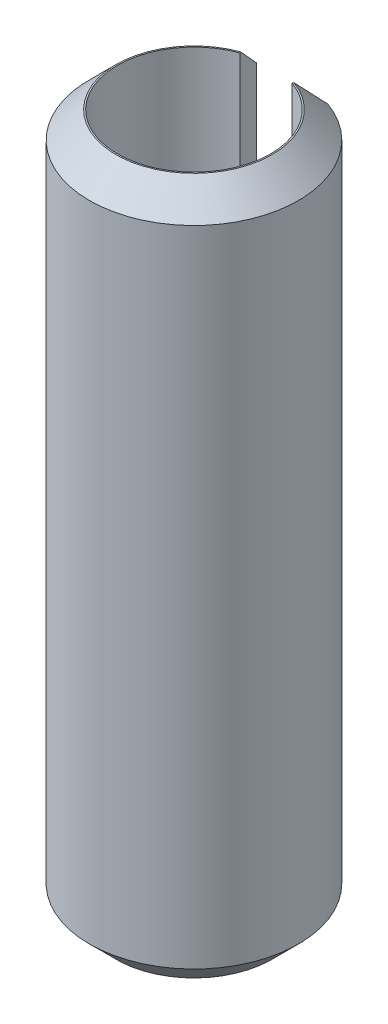
SolidWorks part; units mm, degrees
ref_plane "Top" through (0, 0, 0) normal (0, 0, 1) x (1, 0, 0)
ref_plane "Front" through (0, 0, 0) normal (0, 1, 0) x (1, 0, 0)
ref_plane "Right" through (0, 0, 0) normal (1, 0, 0) x (0, 0, -1)
sketch "Cross Section Sketch" plane through (0, 0, 0) normal (0, 1, 0) x (1, 0, 0)
  line L0 (0.1881, 0.5168) -> (0.2565, 0.7048)
  line L1 (-0.1881, 0.5168) -> (-0.2565, 0.7048)
  line L2 (0, 0) -> (0, 0.5168) construction
  arc A0 (-0.1881, 0.5168) -> (0.1881, 0.5168) centre (0, 0) ccw
  arc A1 (-0.2565, 0.7048) -> (0.2565, 0.7048) centre (0, 0) ccw
  dimension "Outside Diameter" = 1.5
  dimension "D1" = 20
  dimension "D2" = 20
  dimension "Thickness" = 0.2
extrude "Extrude Length" add sketch "Cross Section Sketch" along normal blind 5
chamfer "End Chamfers" distance 0.19 angle 45 2 edges at (0, 0, 0.75) (0, 5, 0.75)
